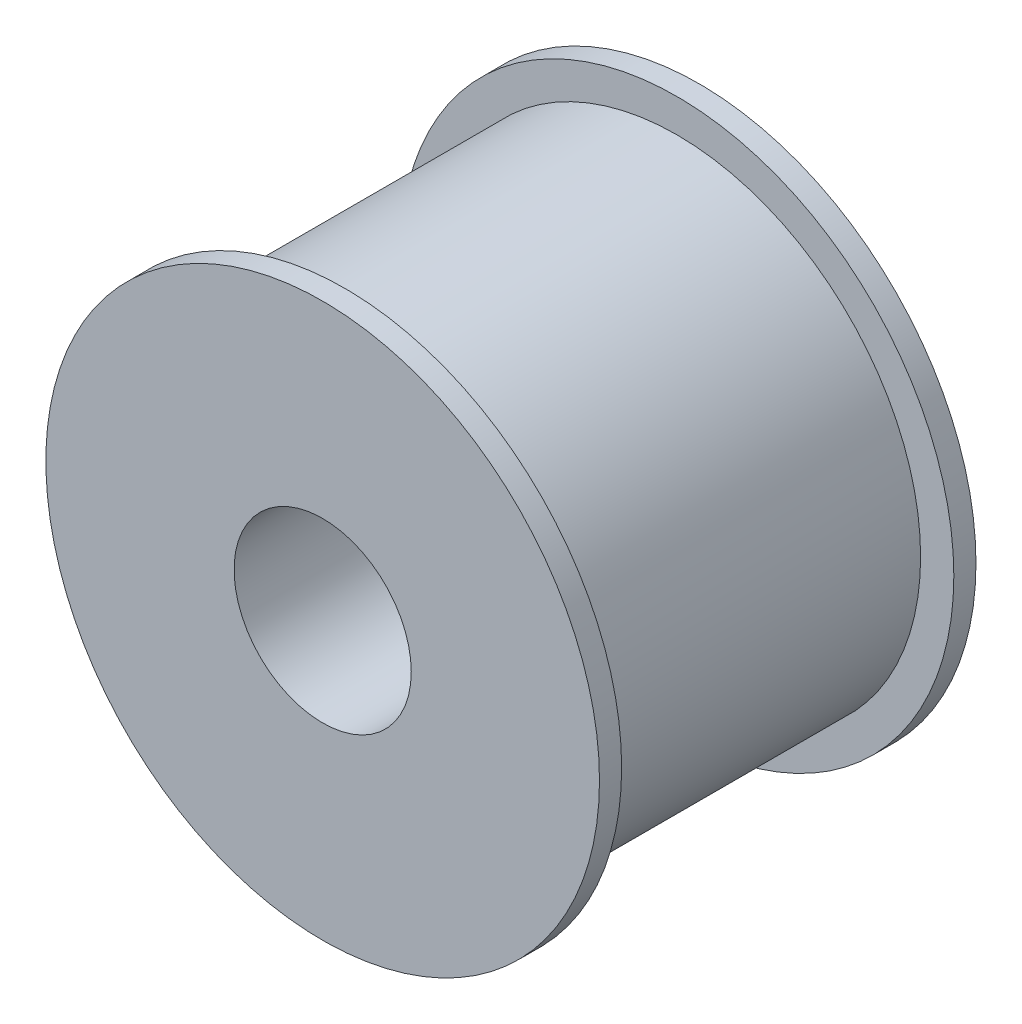
SolidWorks part; units mm, degrees
ref_plane "Front Plane" through (0, 0, 0) normal (0, 0, 1) x (1, 0, 0)
ref_plane "Top Plane" through (0, 0, 0) normal (0, 1, 0) x (1, 0, 0)
ref_plane "Right Plane" through (0, 0, 0) normal (1, 0, 0) x (0, 0, -1)
sketch "Sketch1" plane through (0, 0, 0) normal (0, 0, 1) x (1, 0, 0)
  circle A0 centre (0, 0) radius 11
  circle A1 centre (0, 0) radius 4
  dimension "D1" = 22
  dimension "D2" = 8
extrude "Boss-Extrude1" add sketch "Sketch1" along normal mid plane 16
sketch "Sketch2" plane through (0, 0, 8) normal (0, 0, 1) x (1, 0, 0)
  circle A0 centre (0, 0) radius 4
  circle A1 centre (0, 0) radius 12.5
  dimension "D1" = 25
  dimension "D2" = 8
extrude "Boss-Extrude2" add sketch "Sketch2" along normal mid plane 1
mirror "Mirror1" about plane through (0, 0, 0) normal (0, 0, 1) of "Boss-Extrude2"
